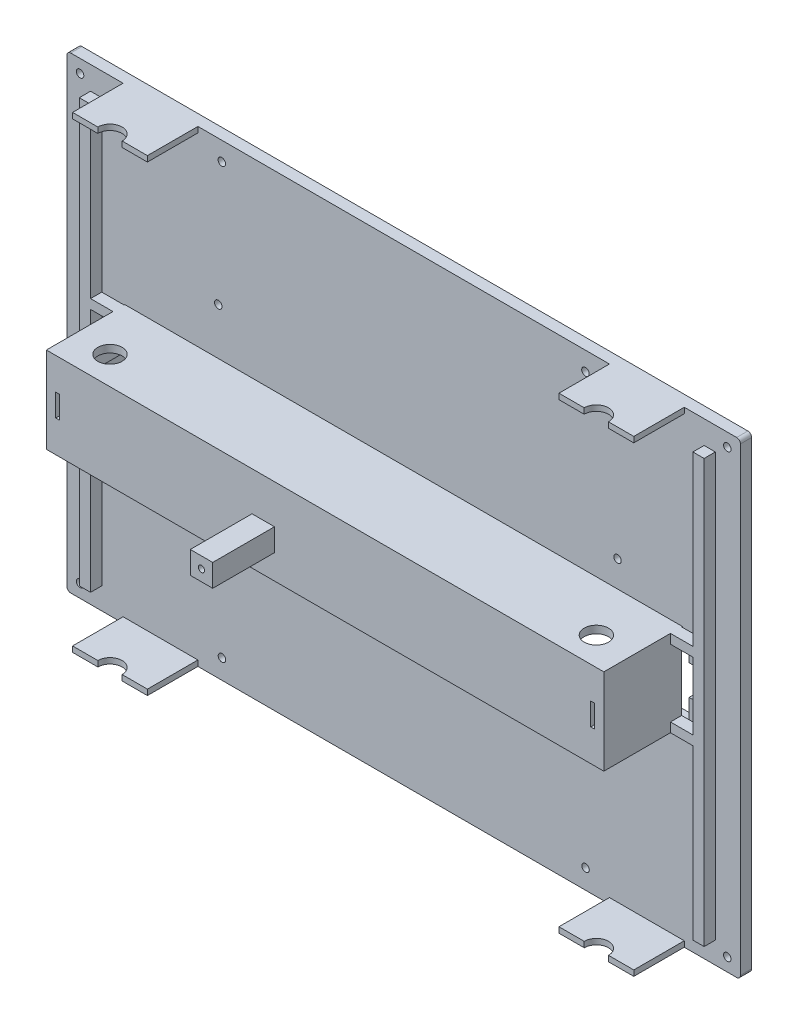
SolidWorks part; units mm, degrees
ref_plane "前视基准面" through (0, 0, 0) normal (0, 0, 1) x (1, 0, 0)
ref_plane "上视基准面" through (0, 0, 0) normal (0, 1, 0) x (1, 0, 0)
ref_plane "右视基准面" through (0, 0, 0) normal (1, 0, 0) x (0, 0, -1)
sketch "草图1" plane through (0, 0, 0) normal (0, 0, 1) x (1, 0, 0)
  line L1 (-90, 62.5) -> (90, 62.5)
  line L2 (-90, 62.5) -> (-90, -62.5)
  line L3 (-90, -62.5) -> (90, -62.5)
  line L4 (90, 62.5) -> (90, -62.5)
  line L5 (-90, 62.5) -> (90, -62.5) construction
  line L6 (-90, -62.5) -> (90, 62.5) construction
  point P0 (0, 0)
  dimension "D1" = 125
  dimension "D2" = 180
extrude "凸台-拉伸1" add sketch "草图1" along normal blind 3
sketch "草图7" plane through (0, 0, 0) normal (0, 0, -1) x (-1, 0, 0)
  line L1 (-72, 10.5) -> (72, 10.5)
  line L2 (-72, 10.5) -> (-72, -10.5)
  line L3 (-72, -10.5) -> (72, -10.5)
  line L4 (72, 10.5) -> (72, -10.5)
  line L5 (0, 0) -> (72.729, 0) construction
  line L8 (0, 0) -> (0, -50.9103) construction
  dimension "D1" = 21
  dimension "D2" = 144
extrude "电池位切除-拉伸3" cut sketch "草图7" against normal up to next
sketch "草图8" plane through (0, 0, 3) normal (0, 0, 1) x (1, 0, 0)
  line L0 (-72, 9.5) -> (72, 9.5)
  line L9 (-72, -9.5) -> (72, -9.5)
  line L10 (72, 0) -> (58.7112, 0) construction
  line L12 (72, 10.5) -> (72, -10.5) construction
  line L13 (-74.5, 11.5) -> (74.5, 11.5)
  line L14 (-74.5, 11.5) -> (-74.5, -11.5)
  line L15 (-74.5, -11.5) -> (74.5, -11.5)
  line L16 (74.5, 11.5) -> (74.5, -11.5)
  line L17 (-72, -10.5) -> (-72, 10.5) construction
  line L18 (-72, 10.5) -> (72, 10.5) construction
  line L19 (-72, 10.5) -> (72, 10.5) construction
  line L22 (72, 9.5) -> (72, -9.5)
  line L23 (-72, -10.5) -> (-72, 10.5) construction
  line L24 (-72, -9.5) -> (-72, 9.5)
  dimension "D1" = 2.5
  dimension "D2" = 2.5
  dimension "D3" = 2
  dimension "D4" = 2
extrude "凸台-拉伸2" add sketch "草图8" along normal blind 21
sketch "草图9" plane through (0, 0, 24) normal (0, 0, 1) x (1, 0, 0)
  line L0 (74.5, 11.5) -> (-74.5, 11.5) construction
  line L5 (74.5, 11.5) -> (-74.5, 11.5)
  line L6 (-74.5, -11.5) -> (74.5, -11.5) construction
  line L7 (-74.5, -11.5) -> (74.5, -11.5)
  line L8 (74.5, -11.5) -> (74.5, 11.5) construction
  line L9 (74.5, -11.5) -> (74.5, 11.5)
  line L10 (-74.5, 11.5) -> (-74.5, -11.5) construction
  line L11 (-74.5, 11.5) -> (-74.5, -11.5)
extrude "凸台-拉伸3" add sketch "草图9" against normal blind 2
sketch "草图4" plane through (0, 0, 0) normal (0, 0, -1) x (-1, 0, 0)
  line L0 (72, -10.5) -> (72, 10.5) construction
  line L5 (72, 0) -> (84.6307, 0) construction
  line L10 (83.2374, -53.4277) -> (79.3374, -53.4277) construction
  line L11 (83.2374, -49.6277) -> (83.2374, -53.4277) construction
  line L12 (79.3374, -49.6277) -> (83.2374, -49.6277) construction
  line L29 (72, -4) -> (74.5, -4)
  line L30 (74.5, -4) -> (74.5, 4)
  line L31 (74.5, 4) -> (72, 4)
  line L32 (72, 4) -> (72, -4)
  dimension "D1" = 8
  dimension "D2" = 2.5
extrude "切除-拉伸2" cut sketch "草图4" against normal blind 2 from offset 1.5 offset against normal yes
sketch "草图10" plane through (0, 0, 24) normal (0, 0, 1) x (1, 0, 0)
  line L0 (-16.5366, -1.9347) -> (8.5541, -1.9347) construction
  line L2 (-19.5366, 1.0653) -> (-19.5366, -4.9347)
  line L4 (-13.5366, 1.0653) -> (-13.5366, -4.9347)
  line L5 (-16.5366, -1.9347) -> (-16.5366, 4.0653) construction
  line L6 (0, 0) -> (60.8594, 0) construction
  line L7 (0, 0) -> (0, 60.5) construction
  line L8 (75, 60.5) -> (-75, 60.5) construction
  line L9 (-19.5366, 1.0653) -> (-13.5366, 1.0653)
  line L10 (-19.5366, -4.9347) -> (-13.5366, -4.9347)
  circle A0 centre (-16.5366, -1.9347) radius 0.825
  dimension "D2" = 1.65
  dimension "D1" = 6
extrude "凸台-拉伸4" add sketch "草图10" along normal up to surface (16.5 mm away)
sketch "草图11" plane through (0, 0, 0) normal (0, 0, -1) x (-1, 0, 0)
  circle A0 centre (-48.6147, -57.3) radius 1 construction
  circle A1 centre (-49.55, -23.8) radius 1 construction
  circle A2 centre (57.15, -18.3) radius 1 construction
  circle A3 centre (48.5747, -57.3) radius 1 construction
  circle A4 centre (86.5, 59) radius 1
  circle A5 centre (48.6147, 57.5) radius 1 construction
  circle A6 centre (-57.15, 18.5) radius 1 construction
  circle A7 centre (-48.5747, 57.5) radius 1 construction
  circle A8 centre (-48.6147, -57.3) radius 1
  circle A9 centre (-49.55, -23.8) radius 1
  circle A10 centre (57.15, -18.3) radius 1
  circle A11 centre (48.5747, -57.3) radius 1
  circle A13 centre (48.6147, 57.5) radius 1
  circle A14 centre (-57.15, 18.5) radius 1
  circle A15 centre (-48.5747, 57.5) radius 1
  circle A16 centre (49.55, 24) radius 1 construction
  circle A17 centre (49.55, 24) radius 1
  circle A18 centre (86.5, -59) radius 1
  circle A19 centre (-86.5, -59) radius 1
  circle A20 centre (-86.5, 59) radius 1
  dimension "D1" = 2
  dimension "D2" = 2
  dimension "D3" = 2
  dimension "D4" = 2
extrude "固定螺丝切除-拉伸3" cut sketch "草图11" against normal up to next
sketch "草图12" plane through (0, 0, 0) normal (0, 0, -1) x (-1, 0, 0)
  circle A0 centre (-48.5747, 57.5) radius 2
  circle A1 centre (-57.15, 18.5) radius 2
  circle A2 centre (-49.55, -23.8) radius 2
  circle A3 centre (-48.6147, -57.3) radius 2
  circle A4 centre (48.5747, -57.3) radius 2
  circle A5 centre (57.15, -18.3) radius 2
  circle A7 centre (-86.5, 59) radius 2
  circle A8 centre (48.6147, 57.5) radius 2
  circle A9 centre (49.55, 24) radius 2
  circle A10 centre (-86.5, -59) radius 2
  circle A11 centre (86.5, -59) radius 2
  circle A12 centre (86.5, 59) radius 2
  dimension "D1" = 4
  dimension "D2" = 4
  dimension "D3" = 4
  dimension "D4" = 4
  dimension "D5" = 4
extrude "固定螺丝凹陷切除-拉伸4" cut sketch "草图12" against normal blind 1.2
fillet "圆角1" radius 1 4 edges at (90, -62.5, 1.5) (-90, -62.5, 1.5) (-90, 62.5, 1.5) (90, 62.5, 1.5)
sketch "草图13" plane through (0, 0, 24) normal (0, 0, 1) x (1, 0, 0)
  line L0 (72, 10.5) -> (72, -10.5) construction
  line L1 (72, 3) -> (71, 3)
  line L2 (72, 3) -> (72, -3)
  line L3 (72, -3) -> (71, -3)
  line L4 (71, 3) -> (71, -3)
  line L5 (-72, -10.5) -> (-72, 10.5) construction
  line L6 (-71, 3) -> (-72, 3)
  line L7 (-71, 3) -> (-71, -3)
  line L8 (-71, -3) -> (-72, -3)
  line L9 (-72, 3) -> (-72, -3)
  line L10 (72, 0) -> (59.7453, 0) construction
  dimension "D1" = 1
  dimension "D2" = 6
  dimension "D3" = 1
  dimension "D4" = 6
extrude "切除-拉伸3" cut sketch "草图13" against normal up to next
sketch "草图14" plane through (0, 0, 22) normal (0, 0, -1) x (-1, 0, 0)
  line L0 (72, 10.5) -> (-72, 10.5) construction
  line L1 (-71, 10.5) -> (-69, 10.5)
  line L2 (-71, 10.5) -> (-71, 5.5)
  line L3 (-71, 5.5) -> (-69, 5.5)
  line L4 (-69, 10.5) -> (-69, 5.5)
  line L5 (-72, 0) -> (-60.8543, 0) construction
  line L6 (-72, 10.5) -> (-72, -10.5) construction
  line L7 (72, 0) -> (63.4917, 0) construction
  line L8 (69, 10.5) -> (71, 10.5)
  line L9 (69, 10.5) -> (69, 6)
  line L10 (69, 6) -> (71, 6)
  line L11 (71, 10.5) -> (71, 6)
  line L12 (72, -10.5) -> (72, 10.5) construction
  line L13 (71, -10.5) -> (71, -6)
  line L14 (69, -6) -> (71, -6)
  line L15 (69, -10.5) -> (69, -6)
  line L16 (69, -10.5) -> (71, -10.5)
  line L17 (-69, -10.5) -> (-69, -5.5)
  line L18 (-71, -5.5) -> (-69, -5.5)
  line L19 (-71, -10.5) -> (-71, -5.5)
  line L20 (-71, -10.5) -> (-69, -10.5)
  dimension "D1" = 1
  dimension "D2" = 2
  dimension "D3" = 4.5
  dimension "D4" = 1
  dimension "D5" = 2
  dimension "D6" = 5
extrude "凸台-拉伸5" add sketch "草图14" along normal blind 16
sketch "草图15" plane through (0, 0, 0) normal (0, 0, -1) x (-1, 0, 0)
  line L0 (72, 10.5) -> (-72, 10.5) construction
  line L5 (72, 10.5) -> (72, -10.5)
  line L7 (-72, -10.5) -> (72, -10.5) construction
  line L8 (-76.3, 10.5) -> (72, 10.5)
  line L9 (-76.3, 10.5) -> (-76.3, 4)
  line L10 (-76.3, -10.5) -> (72, -10.5)
  line L12 (-76.3, 4) -> (-79.3365, 4)
  line L14 (-76.3, -4) -> (-79.3365, -4)
  line L15 (-79.3365, 4) -> (-79.3365, -4)
  line L16 (72, 10.5) -> (-72, 10.5) construction
  line L17 (-76.3, -4) -> (-76.3, -10.5)
  line L18 (-76.1, -10.3) -> (-76.1, 10.3) construction
  line L19 (-79.2365, 3.5) -> (-79.2365, -3.5) construction
  dimension "D1" = 6.5
  dimension "D2" = 6.5
  dimension "D3" = 0.2
  dimension "D4" = 0.1
extrude "切除-拉伸6" cut sketch "草图15" against normal blind 3.2
sketch "草图17" plane through (0, 0, 0) normal (0, 0, -1) x (-1, 0, 0)
  line L0 (-76.3, 4) -> (-79.3365, 4) construction
  line L1 (-81.8365, 4) -> (-79.3365, 4)
  line L2 (-81.8365, 4) -> (-81.8365, -4)
  line L3 (-81.8365, -4) -> (-79.3365, -4)
  line L4 (-79.3365, 4) -> (-79.3365, -4)
  dimension "D1" = 2.5
extrude "切除-拉伸7" cut sketch "草图17" against normal blind 1.5
fillet "圆角2" radius 0.25 26 edges at (-71, 7.75, 6) (-70, 6, 6) (-69, 7.75, 6) (-69, -7.75, 6) (-70, -6, 6) (-71, -7.75, 6) (71, -7.5, 6) (70, -5.5, 6) (69, -7.5, 6) (69, 7.5, 6) (70, 5.5, 6) (71, 7.5, 6) (79.3365, 0, 3) (81.8365, 0, 0) (-69, 9.5, 14) (-71, 9.5, 14) (-71, -9.5, 14) (-69, -9.5, 14) (69, -9.5, 14) (71, -9.5, 14) (71, 9.5, 14) (69, 9.5, 14) (-70, 9.5, 6) (-70, -9.5, 6) (70, -9.5, 6) (70, 9.5, 6)
sketch "草图18" plane through (0, 0, 3) normal (0, 0, 1) x (1, 0, 0)
  line L0 (0, 0) -> (0, 49.5083) construction
  line L1 (-83.5, 56.5) -> (-80.5, 56.5)
  line L2 (-83.5, 56.5) -> (-83.5, -56.5)
  line L3 (-83.5, -56.5) -> (-80.5, -56.5)
  line L4 (-80.5, 56.5) -> (-80.5, 11.5)
  line L5 (89, 62.5) -> (-89, 62.5) construction
  line L6 (-89, -62.5) -> (89, -62.5) construction
  line L7 (-74.5, 11.5) -> (-74.5, -11.5) construction
  line L12 (-80.5, 9) -> (-80.5, -9)
  line L13 (-74.5, 11.5) -> (-80.5, 11.5)
  line L14 (-74.5, 11.5) -> (-74.5, 9)
  line L15 (-74.5, 9) -> (-80.5, 9)
  line L17 (-74.5, -11.5) -> (-80.5, -11.5)
  line L18 (-74.5, -11.5) -> (-74.5, -9)
  line L19 (-74.5, -9) -> (-80.5, -9)
  line L21 (-80.5, -11.5) -> (-80.5, -56.5)
  line L22 (80.5, -11.5) -> (80.5, -56.5)
  line L23 (74.5, -9) -> (80.5, -9)
  line L24 (74.5, -11.5) -> (74.5, -9)
  line L25 (74.5, -11.5) -> (80.5, -11.5)
  line L26 (74.5, 9) -> (80.5, 9)
  line L27 (74.5, 11.5) -> (74.5, 9)
  line L28 (74.5, 11.5) -> (80.5, 11.5)
  line L29 (80.5, 9) -> (80.5, -9)
  line L30 (80.5, 56.5) -> (80.5, 11.5)
  line L31 (83.5, -56.5) -> (80.5, -56.5)
  line L32 (83.5, 56.5) -> (83.5, -56.5)
  line L33 (83.5, 56.5) -> (80.5, 56.5)
  dimension "D1" = 6
  dimension "D2" = 6
  dimension "D3" = 3
  dimension "D4" = 6
  dimension "D5" = 2.5
extrude "凸台-拉伸6" add sketch "草图18" along normal blind 3 from surface at 0.2 starting at face at (0.625, 0, 3.2)
sketch "草图19" plane through (0, 0, 3) normal (0, 0, 1) x (1, 0, 0)
  line L0 (-89, -62.5) -> (89, -62.5) construction
  line L1 (-75, -61) -> (-55, -61)
  line L2 (-75, -61) -> (-75, -62.5)
  line L3 (-75, -62.5) -> (-55, -62.5)
  line L4 (-55, -61) -> (-55, -62.5)
  line L5 (65, -71.3) -> (65, -63.3504) construction
  line L6 (55, -61) -> (75, -61)
  line L7 (55, -61) -> (55, -62.5)
  line L8 (55, -62.5) -> (75, -62.5)
  line L9 (75, -61) -> (75, -62.5)
  line L10 (66.9391, -71.3) -> (63.0609, -71.3) construction
  line L11 (-65, -71.3) -> (-65, -63.3504) construction
  line L12 (-63.0609, -71.3) -> (-66.9391, -71.3) construction
  line L13 (90, 0) -> (165.2709, 0) construction
  line L14 (90, -61.5) -> (90, 61.5) construction
  line L15 (-65, 71.3) -> (-65, 63.3504) construction
  line L16 (65, 71.3) -> (65, 63.3504) construction
  line L17 (75, 61) -> (75, 62.5)
  line L18 (55, 62.5) -> (75, 62.5)
  line L19 (55, 61) -> (55, 62.5)
  line L20 (55, 61) -> (75, 61)
  line L21 (-55, 61) -> (-55, 62.5)
  line L22 (-75, 62.5) -> (-55, 62.5)
  line L23 (-75, 61) -> (-75, 62.5)
  line L24 (-75, 61) -> (-55, 61)
  dimension "D1" = 20
  dimension "D2" = 1.5
extrude "凸台-拉伸7" add sketch "草图19" along normal blind 13.5
sketch "草图20" plane through (0, -62.5, 0) normal (0, -1, 0) x (1, 0, 0)
  line L0 (-75, 16.5) -> (-55, 16.5) construction
  line L1 (55, 16.5) -> (75, 16.5) construction
  circle A0 centre (-65, 16.5) radius 3.25
  arc A1 (-63.0609, 14.55) -> (-63.0609, 18.45) centre (-65, 16.5) ccw construction
  circle A2 centre (65, 16.5) radius 3.25
  arc A3 (66.9391, 14.55) -> (66.9391, 18.45) centre (65, 16.5) ccw construction
  dimension "D1" = 0.5
  dimension "D2" = 0.5
extrude "切除-拉伸8" cut sketch "草图20" against normal up to surface (125 mm away)
